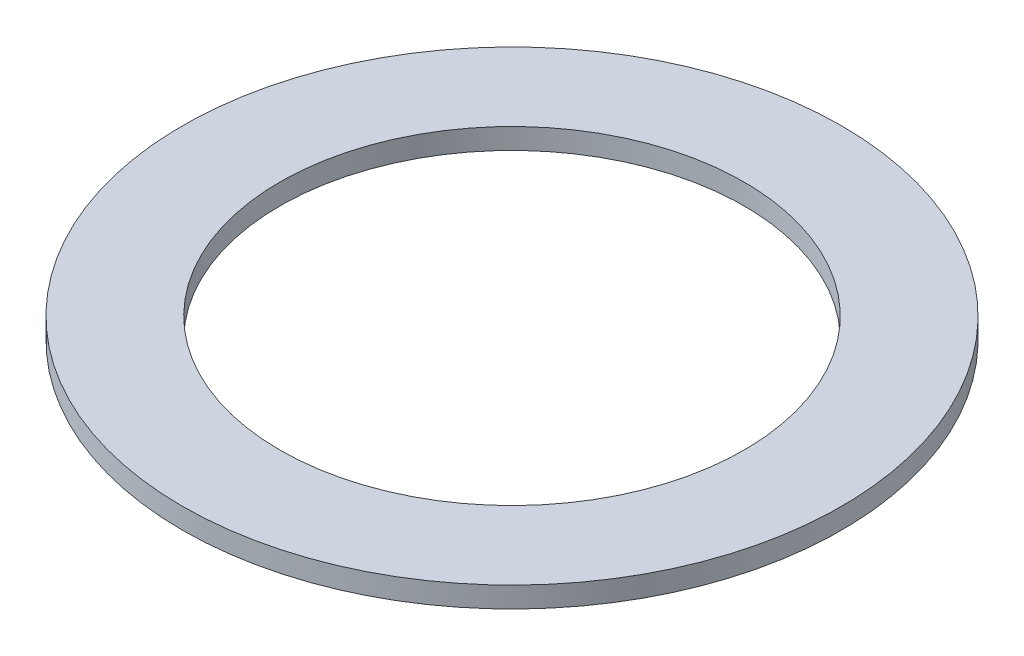
SolidWorks part; units mm, degrees
ref_plane "Front Plane" through (0, 0, 0) normal (0, 0, 1) x (1, 0, 0)
ref_plane "Top Plane" through (0, 0, 0) normal (0, 1, 0) x (1, 0, 0)
ref_plane "Right Plane" through (0, 0, 0) normal (1, 0, 0) x (0, 0, -1)
sketch "Sketch1" plane through (0, 0, 0) normal (0, 1, 0) x (1, 0, 0)
  circle A0 centre (0, 0) radius 7.95
  circle A1 centre (0, 0) radius 5.6
  dimension "D1" = 15.9
  dimension "D2" = 11.2
extrude "Boss-Extrude1" add sketch "Sketch1" along normal blind 0.5
